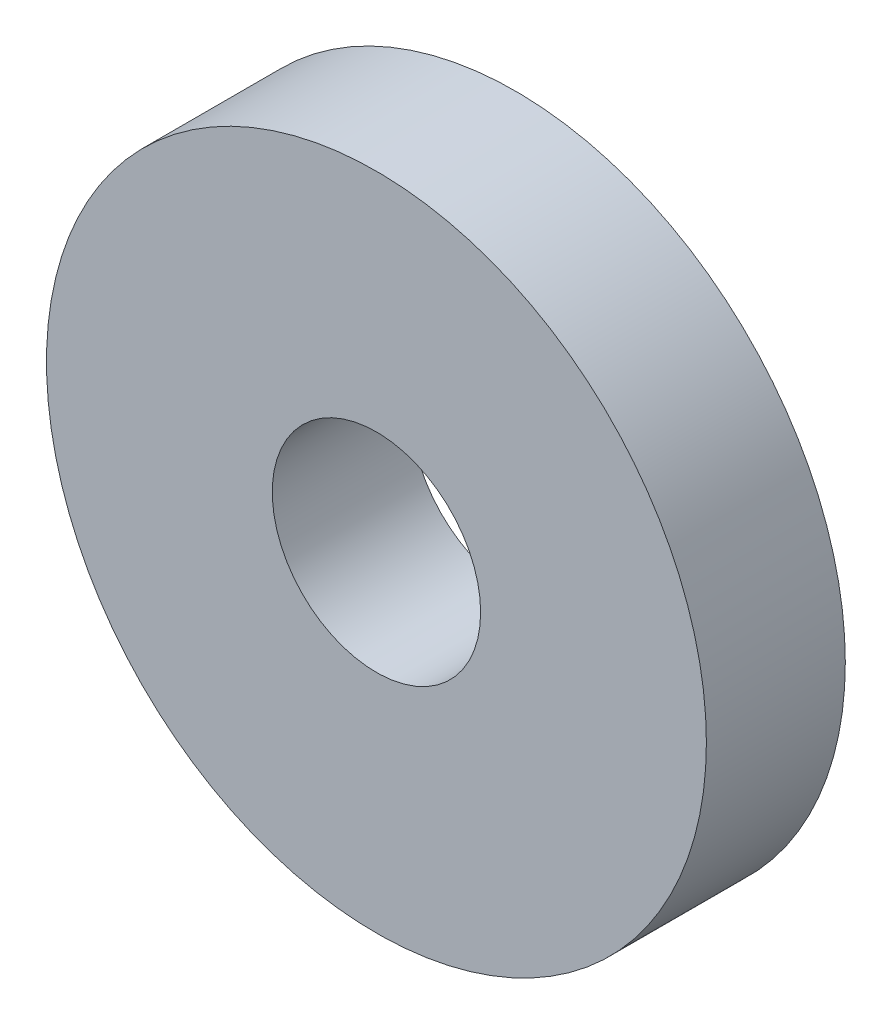
SolidWorks part; units mm, degrees
ref_plane "前视基准面" through (0, 0, 0) normal (0, 0, 1) x (1, 0, 0)
ref_plane "上视基准面" through (0, 0, 0) normal (0, 1, 0) x (1, 0, 0)
ref_plane "右视基准面" through (0, 0, 0) normal (1, 0, 0) x (0, 0, -1)
sketch "草图1" plane through (0, 0, 0) normal (0, 0, 1) x (1, 0, 0)
  circle A0 centre (0, 0) radius 3
  circle A1 centre (0, 0) radius 9.5
  dimension "D1" = 6
  dimension "D2" = 19
extrude "凸台-拉伸1" add sketch "草图1" along normal blind 4
